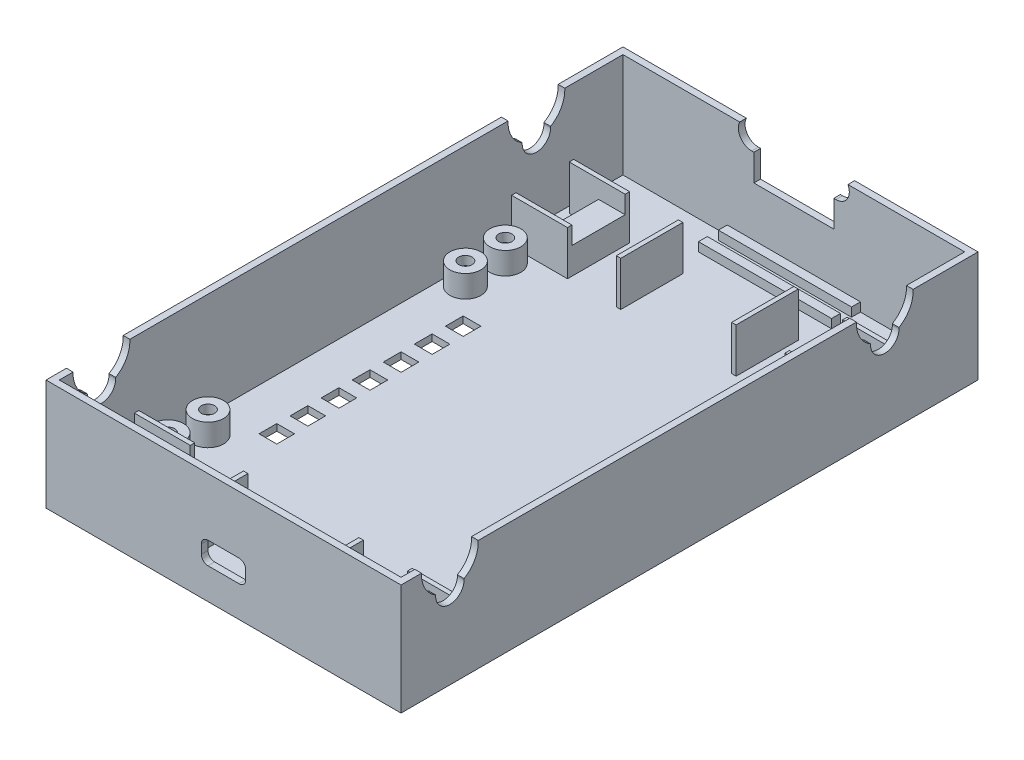
SolidWorks part; units mm, degrees
ref_plane "Спереди" through (0, 0, 0) normal (0, 0, 1) x (1, 0, 0)
ref_plane "Сверху" through (0, 0, 0) normal (0, 1, 0) x (1, 0, 0)
ref_plane "Справа" through (0, 0, 0) normal (1, 0, 0) x (0, 0, -1)
other "Configuration Table"
sketch "Корпус" plane through (0, 0, 0) normal (0, 1, 0) x (1, 0, 0)
  line L1 (40, -65) -> (-40, -65)
  line L2 (40, -65) -> (40, 65)
  line L3 (40, 65) -> (-40, 65)
  line L4 (-40, -65) -> (-40, 65)
  line L5 (40, -65) -> (-40, 65) construction
  line L6 (40, 65) -> (-40, -65) construction
  point P0 (0, 0)
  dimension "D1" = 80
  dimension "D2" = 130
sketch3d "Трехмерный эскиз1" plane through (0, 0, 0) normal (0, 0, 1) x (1, 0, 0)
extrude "Бобышка-Вытянуть1" add sketch "Корпус" along normal blind 25
sketch "Эскиз1" plane through (0, 25, 0) normal (0, 1, 0) x (1, 0, 0)
  line L0 (40, 65) -> (-40, 65) construction
  line L5 (-38.5, 63.5) -> (38.5, 63.5)
  line L6 (-38.5, 63.5) -> (-38.5, -63.5)
  line L7 (-38.5, -63.5) -> (38.5, -63.5)
  line L8 (38.5, 63.5) -> (38.5, -63.5)
  line L9 (-38.5, 63.5) -> (38.5, -63.5) construction
  line L10 (-38.5, -63.5) -> (38.5, 63.5) construction
  line L11 (-40, 65) -> (-40, -65) construction
  point P0 (0, 0)
  dimension "D1" = 1.5
  dimension "D2" = 1.5
extrude "Вырез-Вытянуть1" cut sketch "Эскиз1" against normal offset from surface (23.5 mm away) 1.5 up to face at (0, 0, 0)
sketch "Эскиз2" plane through (0, 0, -63.5) normal (0, 0, 1) x (1, 0, 0)
  line L0 (-14.3, 33.5) -> (14.3, 33.5) construction
  line L5 (-9, 26.7) -> (-9, 32.7)
  line L6 (-9, 32.7) -> (9, 32.7)
  line L7 (14.3, 33.5) -> (14.3, 4.5) construction
  line L8 (14.3, 4.5) -> (-14.3, 4.5) construction
  line L9 (-14.3, 4.5) -> (-14.3, 33.5) construction
  line L10 (0, 33.5) -> (0, 4.5) construction
  line L11 (9, 32.7) -> (9, 26.7)
  line L12 (9, 26.7) -> (9.5, 26.7)
  line L13 (-9, 26.7) -> (-9.5, 26.7)
  line L14 (9.5, 20.7) -> (9, 20.7)
  line L15 (9, 20.7) -> (9, 14.7)
  line L16 (9, 14.7) -> (-9, 14.7)
  line L17 (-9, 14.7) -> (-9, 20.7)
  line L18 (-9, 20.7) -> (-9.5, 20.7)
  line L20 (-12.5, 23.7) -> (12.5, 23.7) construction
  line L21 (-38.5, 1.5) -> (-38.5, 25) construction
  line L22 (38.5, 25) -> (-38.5, 25) construction
  line L23 (-40, 25) -> (40, 25) construction
  line L24 (0, 0) -> (0, 25) construction
  line L25 (-40, 0) -> (40, 0) construction
  arc A4 (-9.5, 26.7) -> (-9.5, 20.7) centre (-9.5, 23.7) ccw
  arc A5 (9.5, 26.7) -> (9.5, 20.7) centre (9.5, 23.7) cw
  point P32 (0, 23.7)
  dimension "D2" = 4.5
  dimension "D3" = 25
  dimension "D4" = 3
  dimension "D5" = 28.6
  dimension "D6" = 28.6
  dimension "D7" = 29
  dimension "D8" = 18
  dimension "D9" = 9.8
  dimension "D10" = 18
  dimension "D11" = 6
  dimension "D12" = 19.2
extrude "Вырез-Вытянуть2" cut sketch "Эскиз2" against normal blind 2
sketch "Эскиз3" plane through (-40, 0, 0) normal (-1, 0, 0) x (0, 0, 1)
  line L1 (-50, 34.7) -> (-38, 34.7) construction
  line L2 (-50, 34.7) -> (-50, 2.5) construction
  line L3 (-50, 2.5) -> (-38, 2.5) construction
  line L4 (-38, 34.7) -> (-38, 2.5) construction
  line L5 (-50, 34.7) -> (-38, 2.5) construction
  line L6 (-50, 2.5) -> (-38, 34.7) construction
  line L7 (-44, 34.7) -> (-44, 2.5) construction
  line L8 (-44, 28.9) -> (-44, 15.7) construction
  line L9 (-47.2, 18.9) -> (-47.2, 19.1574)
  line L10 (-65, 25) -> (-65, 0) construction
  line L12 (-65, 0) -> (65, 0) construction
  line L13 (-47.2, 18.9) -> (-47.2, 19.1574)
  line L14 (-40.8, 18.9) -> (-40.8, 19.1574)
  line L15 (-40.8, 18.9) -> (-40.8, 19.1574)
  line L16 (0, 0) -> (0, 25) construction
  line L17 (-65, 25) -> (65, 25) construction
  arc A1 (-47.2, 18.9) -> (-40.8, 18.9) centre (-44, 18.9) ccw
  arc A2 (-40.8, 19.1574) -> (-47.2, 19.1574) centre (-44, 24.7) ccw
  point P0 (-44, 18.6)
  dimension "D3" = 6.4
  dimension "D4" = 3.2
  dimension "D5" = 5.8
  dimension "D1" = 32.2
  dimension "D2" = 12
  dimension "D6" = 10
  dimension "D7" = 15
  dimension "D8" = 2.5
extrude "Вырез-Вытянуть3" cut sketch "Эскиз3" against normal blind 1.5
sketch "Эскиз5" plane through (-40, 0, 0) normal (-1, 0, 0) x (0, 0, 1)
  line L0 (0, 0) -> (0, 25) construction
  line L1 (-37.607, 25) -> (65, 25) construction
  line L2 (48, 34.7) -> (60, 34.7) construction
  line L3 (48, 34.7) -> (48, 2.5) construction
  line L6 (48, 2.5) -> (60, 2.5) construction
  line L8 (60, 34.7) -> (60, 2.5) construction
  line L9 (48, 34.7) -> (60, 2.5) construction
  line L10 (48, 2.5) -> (60, 34.7) construction
  line L11 (54, 34.7) -> (54, 2.5) construction
  line L12 (54, 28.9) -> (54, 15.7) construction
  line L13 (50.8, 18.9) -> (50.8, 19.1574)
  line L15 (50.8, 18.9) -> (50.8, 19.1574)
  line L16 (57.2, 18.9) -> (57.2, 19.1574)
  line L17 (57.2, 18.9) -> (57.2, 19.1574)
  line L18 (-65, 0) -> (65, 0) construction
  line L19 (65, 25) -> (65, 0) construction
  arc A0 (50.8, 18.9) -> (57.2, 18.9) centre (54, 18.9) ccw
  arc A1 (57.2, 19.1574) -> (50.8, 19.1574) centre (54, 24.7) ccw
  point P5 (54, 18.6)
  dimension "D1" = 32.2
  dimension "D2" = 12
  dimension "D5" = 6.4
  dimension "D6" = 3.2
  dimension "D4" = 10
  dimension "D7" = 5.8
  dimension "D8" = 2.5
  dimension "D9" = 5
extrude "Вырез-Вытянуть4" cut sketch "Эскиз5" against normal up to body (1.5 mm away) from surface at 0 contours A1 L13 A0 L16 starting at face at (-40, 17.2019, -26.4)
sketch "Эскиз6" plane through (40, 0, 0) normal (1, 0, 0) x (0, 0, -1)
  line L0 (-60, 34.7) -> (-48, 34.7) construction
  line L1 (-60, 34.7) -> (-60, 2.5) construction
  line L2 (-60, 2.5) -> (-48, 2.5) construction
  line L3 (-48, 34.7) -> (-48, 2.5) construction
  line L4 (-60, 34.7) -> (-48, 2.5) construction
  line L5 (-60, 2.5) -> (-48, 34.7) construction
  line L6 (-54, 34.7) -> (-54, 2.5) construction
  line L7 (-54, 29.4) -> (-54, 15.7) construction
  line L8 (-57.2, 18.9) -> (-57.2, 19.1574)
  line L9 (-50.8, 18.9) -> (-50.8, 19.1574)
  line L12 (-65, 25) -> (-65, 0) construction
  line L13 (-65, 0) -> (65, 0) construction
  arc A0 (-57.2, 18.9) -> (-50.8, 18.9) centre (-54, 18.9) ccw
  arc A1 (-50.8, 19.1574) -> (-57.2, 19.1574) centre (-54, 24.7) ccw
  point P0 (-54, 18.6)
  dimension "D5" = 6.4
  dimension "D6" = 3.2
  dimension "D1" = 32.2
  dimension "D2" = 12
  dimension "D3" = 5.8
  dimension "D4" = 10
  dimension "D8" = 5
  dimension "D9" = 2.5
extrude "Вырез-Вытянуть5" cut sketch "Эскиз6" against normal up to surface (1.5 mm away) from surface at 0 up to face at (38.5, 13.25, 0) starting at face at (40, 12.5, 0)
sketch "Эскиз9" plane through (40, 0, 0) normal (1, 0, 0) x (0, 0, -1)
  line L0 (38, 34.7) -> (50, 34.7) construction
  line L1 (38, 34.7) -> (38, 2.5) construction
  line L2 (38, 2.5) -> (50, 2.5) construction
  line L3 (50, 34.7) -> (50, 2.5) construction
  line L4 (38, 34.7) -> (50, 2.5) construction
  line L5 (38, 2.5) -> (50, 34.7) construction
  line L6 (44, 34.7) -> (44, 2.5) construction
  line L7 (44, 28.9) -> (44, 15.7) construction
  line L8 (40.8, 18.9) -> (40.8, 19.1574)
  line L9 (40.8, 18.9) -> (40.8, 19.1574)
  line L10 (47.2, 18.9) -> (47.2, 19.1574)
  line L11 (47.2, 18.9) -> (47.2, 19.1574)
  line L12 (65, 25) -> (65, 0) construction
  line L13 (-65, 0) -> (65, 0) construction
  arc A0 (40.8, 18.9) -> (47.2, 18.9) centre (44, 18.9) ccw
  arc A1 (47.2, 19.1574) -> (40.8, 19.1574) centre (44, 24.7) ccw
  point P0 (44, 18.6)
  dimension "D5" = 6.4
  dimension "D6" = 3.2
  dimension "D1" = 32.2
  dimension "D2" = 12
  dimension "D3" = 5.8
  dimension "D4" = 10
  dimension "D8" = 15
  dimension "D9" = 2.5
extrude "Вырез-Вытянуть7" cut sketch "Эскиз9" against normal up to surface (1.5 mm away) from surface at 0 contours A1 L8 A0 L10 up to face at (38.5, 17.5019, 32.4) starting at face at (40, 17.2019, 32.4)
sketch "Эскиз10" plane through (0, 1.5, 0) normal (0, 1, 0) x (1, 0, 0)
  line L0 (-40, 44) -> (40, 44) construction
  line L3 (-40, -54) -> (40, -54) construction
  line L4 (-40, -50.8) -> (-40, -57.2) construction
  line L5 (40, -57.2) -> (40, -50.8) construction
  line L6 (-38.5, -63.5) -> (-38.5, 63.5) construction
  line L7 (-30.5, 38) -> (-24.5, 38)
  line L8 (-30.5, 38) -> (-30.5, 50)
  line L9 (-30.5, 50) -> (-24.5, 50)
  line L10 (-24.5, 38) -> (-24.5, 50)
  line L11 (-30.5, 38) -> (-24.5, 50) construction
  line L12 (-30.5, 50) -> (-24.5, 38) construction
  line L13 (24.5, 38) -> (30.5, 38)
  line L14 (24.5, 38) -> (24.5, 50)
  line L15 (24.5, 50) -> (30.5, 50)
  line L16 (30.5, 38) -> (30.5, 50)
  line L17 (24.5, 38) -> (30.5, 50) construction
  line L18 (24.5, 50) -> (30.5, 38) construction
  line L20 (-30.5, -60) -> (-24.5, -60)
  line L21 (-30.5, -60) -> (-30.5, -48)
  line L22 (-30.5, -48) -> (-24.5, -48)
  line L23 (-24.5, -60) -> (-24.5, -48)
  line L24 (-30.5, -60) -> (-24.5, -48) construction
  line L25 (-30.5, -48) -> (-24.5, -60) construction
  line L26 (24.5, -60) -> (30.5, -60)
  line L27 (24.5, -60) -> (24.5, -48)
  line L28 (24.5, -48) -> (30.5, -48)
  line L29 (30.5, -60) -> (30.5, -48)
  line L30 (24.5, -60) -> (30.5, -48) construction
  line L31 (24.5, -48) -> (30.5, -60) construction
  line L34 (-12.2037, 65) -> (-40, 65) construction
  line L35 (0, 65) -> (0, -65) construction
  line L36 (-9, 65) -> (9, 65) construction
  line L37 (-40, -65) -> (40, -65) construction
  line L38 (38.5, 63.5) -> (38.5, -63.5) construction
  point P4 (0, 44)
  point P12 (-27.5, 44)
  point P19 (27.5, 44)
  point P24 (30.5, 44)
  point P27 (-27.5, -54)
  point P32 (27.5, -54)
  point P37 (30.5, -54)
  point P38 (0, -54)
  point P46 (-30.5, -54)
  dimension "D1" = 12
  dimension "D2" = 98
  dimension "D3" = 6
  dimension "D4" = 6
  dimension "D5" = 12
  dimension "D6" = 8
  dimension "D7" = 12
  dimension "D8" = 6
  dimension "D9" = 6
  dimension "D10" = 12
  dimension "D11" = 8
  dimension "D12" = 8
  dimension "D13" = 21
  dimension "D14" = 8
extrude "Бобышка-Вытянуть2" add sketch "Эскиз10" along normal blind 6
sketch "Эскиз11" plane through (0, 1.5, 0) normal (0, 1, 0) x (1, 0, 0)
  line L0 (-24.5, 50) -> (-24.5, 51)
  line L1 (-24.5, 51) -> (-37.1, 51)
  line L2 (37.1, 50) -> (37.1, 51)
  line L3 (-24.5, 50) -> (-37.1, 50)
  line L4 (-37.1, 50) -> (-37.1, 51)
  line L5 (-24.5, 38) -> (-37.1, 38)
  line L6 (37.1, 51) -> (24.5, 51)
  line L7 (-37.1, 38) -> (-37.1, 37)
  line L8 (37.1, 50) -> (24.5, 50)
  line L9 (-37.1, 37) -> (-24.5, 37)
  line L10 (-24.5, 37) -> (-24.5, 38)
  line L11 (24.5, 50) -> (24.5, 51)
  line L12 (37.1, 38) -> (24.5, 38)
  line L13 (24.5, 38) -> (24.5, 37)
  line L14 (24.5, 37) -> (37.1, 37)
  line L15 (37.1, 37) -> (37.1, 38)
  line L16 (37.1, -48) -> (37.1, -47)
  line L17 (37.1, -47) -> (24.5, -47)
  line L18 (37.1, -48) -> (24.5, -48)
  line L19 (24.5, -48) -> (24.5, -47)
  line L20 (37.1, -60) -> (24.5, -60)
  line L21 (24.5, -60) -> (24.5, -61)
  line L22 (24.5, -61) -> (37.1, -61)
  line L23 (37.1, -61) -> (37.1, -60)
  line L24 (-24.5, -48) -> (-24.5, -47)
  line L25 (-24.5, -47) -> (-37.1, -47)
  line L26 (-24.5, -48) -> (-37.1, -48)
  line L27 (-37.1, -48) -> (-37.1, -47)
  line L28 (-24.5, -60) -> (-37.1, -60)
  line L29 (-37.1, -60) -> (-37.1, -61)
  line L30 (-37.1, -61) -> (-24.5, -61)
  line L31 (-24.5, -61) -> (-24.5, -60)
  dimension "D1" = 1
  dimension "D2" = 12.6
  dimension "D3" = 12.6
  dimension "D4" = 1
  dimension "D5" = 12.6
  dimension "D6" = 1
  dimension "D7" = 12.6
  dimension "D8" = 1
extrude "Бобышка-Вытянуть3" add sketch "Эскиз11" along normal blind 10
sketch "Эскиз13" plane through (0, 1.5, 0) normal (0, 1, 0) x (1, 0, 0)
  line L0 (-10, -63.5) -> (10, -63.5) construction
  line L1 (-40, -5) -> (40, -5) construction
  line L2 (10, -63.5) -> (10, -36.5) construction
  line L3 (10, -36.5) -> (37, -36.5) construction
  line L4 (37, -36.5) -> (37, 26.5) construction
  line L5 (37, 26.5) -> (-37, 26.5) construction
  line L6 (-40, -65) -> (40, -65) construction
  line L7 (-37, 26.5) -> (-37, -36.5) construction
  line L8 (-37, -36.5) -> (-10, -36.5) construction
  line L9 (-10, -36.5) -> (-10, -63.5) construction
  line L10 (-38.5, -63.5) -> (38.5, -63.5) construction
  line L11 (-40, 44) -> (-40, -54) construction
  line L12 (-40, 47.2) -> (-40, 40.8) construction
  line L14 (-40, -50.8) -> (-40, -57.2) construction
  circle A0 centre (-34.5, 24) radius 3.5
  circle A2 centre (34.5, 24) radius 3.5
  circle A3 centre (-34.5, -34) radius 3.5
  circle A4 centre (34.5, -34) radius 3.5
  circle A8 centre (-34.5, 33) radius 3.5
  circle A9 centre (34.5, 33) radius 3.5
  circle A10 centre (-34.5, -43) radius 3.5
  circle A11 centre (34.5, -43) radius 3.5
  circle A12 centre (0, -54) radius 3.5
  point P2 (0, -63.5)
  point P9 (0, -63.5)
  point P45 (-40, -5)
  dimension "D5" = 29
  dimension "D6" = 2.5
  dimension "D8" = 7
  dimension "D11" = 7
  dimension "D16" = 7
  dimension "D17" = 7
  dimension "D18" = 27
  dimension "D25" = 7
  dimension "D26" = 7
  dimension "D28" = 7
  dimension "D30" = 7
  dimension "D1" = 20
  dimension "D4" = 29
  dimension "D7" = 2.5
  dimension "D9" = 2.5
  dimension "D10" = 2.5
  dimension "D12" = 2.5
  dimension "D13" = 2.5
  dimension "D14" = 2.5
  dimension "D15" = 2.5
  dimension "D19" = 9.5
  dimension "D23" = 29
  dimension "D24" = 9
  dimension "D27" = 9
  dimension "D29" = 9
  dimension "D31" = 9
  dimension "D32" = 22
  dimension "D33" = 69
  dimension "D34" = 76
extrude "Бобышка-Вытянуть4" add sketch "Эскиз13" along normal blind 5
sketch "Эскиз14" plane through (0, 0, 0) normal (0, -1, 0) x (1, 0, 0)
  circle A2 centre (-34.5, 34) radius 2.5
  circle A3 centre (34.5, 34) radius 2.5
  circle A4 centre (-34.5, -24) radius 2.5
  circle A5 centre (34.5, -24) radius 2.5
  circle A6 centre (-34.5, -33) radius 2.5
  circle A7 centre (34.5, -33) radius 2.5
  circle A8 centre (34.5, 43) radius 2.5
  circle A9 centre (-34.5, 43) radius 2.5
  circle A10 centre (0, 54) radius 2.5
  dimension "D2" = 5
  dimension "D3" = 5
  dimension "D4" = 5
  dimension "D5" = 5
  dimension "D6" = 5
  dimension "D7" = 5
  dimension "D8" = 5
  dimension "D9" = 5
  dimension "D10" = 5
extrude "Вырез-Вытянуть8" cut sketch "Эскиз14" against normal offset from surface (4.5 mm away) 2 up to face at (-34.5, 6.5, -20.5)
sketch "Эскиз15" plane through (0, 6.5, 0) normal (0, 1, 0) x (1, 0, 0)
  circle A0 centre (-34.5, 24) radius 1.5
  circle A1 centre (34.5, 24) radius 1.5
  circle A2 centre (-34.5, -34) radius 1.5
  circle A3 centre (34.5, -34) radius 1.5
  circle A6 centre (-34.5, 33) radius 1.5
  circle A7 centre (34.5, 33) radius 1.5
  circle A9 centre (-34.5, -43) radius 1.5
  circle A11 centre (34.5, -43) radius 1.5
  circle A12 centre (0, -54) radius 1.5
  dimension "D1" = 3
  dimension "D2" = 3
  dimension "D3" = 3
  dimension "D4" = 3
  dimension "D5" = 3
  dimension "D7" = 3
  dimension "D8" = 3
  dimension "D9" = 3
  dimension "D10" = 3
extrude "Вырез-Вытянуть9" cut sketch "Эскиз15" against normal up to next
fillet "Скругление1" radius 1 9 edges at (34.5, 0, 31.5) (-34.5, 0, 31.5) (-34.5, 0, -26.5) (34.5, 0, -26.5) (34.5, 0, 40.5) (-34.5, 0, 40.5) (-34.5, 0, -35.5) (34.5, 0, -35.5) (0, 0, 51.5)
sketch "Эскиз16" plane through (0, 1.5, 0) normal (0, 1, 0) x (1, 0, 0)
  line L0 (-29, 11) -> (-25, 11)
  line L5 (-29, 18) -> (-25, 18)
  line L6 (-29, 18) -> (-29, 14)
  line L7 (-29, 14) -> (-25, 14)
  line L8 (-25, 18) -> (-25, 14)
  line L9 (-29, 18) -> (-25, 14) construction
  line L10 (-29, 14) -> (-25, 18) construction
  line L11 (-29, 11) -> (-29, 7)
  line L12 (-29, 7) -> (-25, 7)
  line L13 (-25, 11) -> (-25, 7)
  line L14 (-29, 11) -> (-25, 7) construction
  line L15 (-29, 7) -> (-25, 11) construction
  line L16 (0, 65) -> (0, -65) construction
  line L17 (-9, 65) -> (9, 65) construction
  line L18 (-40, -65) -> (40, -65) construction
  line L19 (-29, -3) -> (-25, -3)
  line L20 (-29, 4) -> (-25, 4)
  line L21 (-29, 4) -> (-29, 0)
  line L22 (-29, 0) -> (-25, 0)
  line L23 (-25, 4) -> (-25, 0)
  line L24 (-29, 4) -> (-25, 0) construction
  line L25 (-29, 0) -> (-25, 4) construction
  line L26 (-29, -3) -> (-29, -7)
  line L27 (-29, -7) -> (-25, -7)
  line L28 (-25, -3) -> (-25, -7)
  line L29 (-29, -3) -> (-25, -7) construction
  line L30 (-29, -7) -> (-25, -3) construction
  line L31 (-29, -17) -> (-25, -17)
  line L32 (-29, -10) -> (-25, -10)
  line L33 (-29, -10) -> (-29, -14)
  line L34 (-29, -14) -> (-25, -14)
  line L35 (-25, -10) -> (-25, -14)
  line L36 (-29, -10) -> (-25, -14) construction
  line L37 (-29, -14) -> (-25, -10) construction
  line L38 (-29, -17) -> (-29, -21)
  line L39 (-29, -21) -> (-25, -21)
  line L40 (-25, -17) -> (-25, -21)
  line L41 (-29, -17) -> (-25, -21) construction
  line L42 (-29, -21) -> (-25, -17) construction
  line L44 (-29, -24) -> (-25, -24)
  line L45 (-29, -24) -> (-29, -28)
  line L46 (-29, -28) -> (-25, -28)
  line L47 (-25, -24) -> (-25, -28)
  line L48 (-29, -24) -> (-25, -28) construction
  line L49 (-29, -28) -> (-25, -24) construction
  line L53 (-40, -5) -> (40, -5) construction
  line L56 (29, -28) -> (25, -24) construction
  line L57 (29, -24) -> (25, -28) construction
  line L58 (29, -21) -> (25, -17) construction
  line L59 (29, -17) -> (25, -21) construction
  line L60 (29, -14) -> (25, -10) construction
  line L61 (29, -10) -> (25, -14) construction
  line L62 (29, -7) -> (25, -3) construction
  line L63 (29, -3) -> (25, -7) construction
  line L64 (29, 0) -> (25, 4) construction
  line L65 (29, 4) -> (25, 0) construction
  line L66 (29, 7) -> (25, 11) construction
  line L67 (29, 11) -> (25, 7) construction
  line L68 (29, 14) -> (25, 18) construction
  line L69 (29, 18) -> (25, 14) construction
  line L70 (25, -24) -> (25, -28)
  line L71 (29, -28) -> (25, -28)
  line L72 (29, -24) -> (29, -28)
  line L73 (29, -24) -> (25, -24)
  line L74 (25, -17) -> (25, -21)
  line L75 (29, -21) -> (25, -21)
  line L76 (29, -17) -> (29, -21)
  line L77 (25, -10) -> (25, -14)
  line L78 (29, -14) -> (25, -14)
  line L79 (29, -10) -> (29, -14)
  line L80 (29, -10) -> (25, -10)
  line L81 (29, -17) -> (25, -17)
  line L82 (25, -3) -> (25, -7)
  line L83 (29, -7) -> (25, -7)
  line L84 (29, -3) -> (29, -7)
  line L85 (25, 4) -> (25, 0)
  line L86 (29, 0) -> (25, 0)
  line L87 (29, 4) -> (29, 0)
  line L88 (29, 4) -> (25, 4)
  line L89 (29, -3) -> (25, -3)
  line L90 (25, 11) -> (25, 7)
  line L91 (29, 7) -> (25, 7)
  line L92 (29, 11) -> (29, 7)
  line L93 (25, 18) -> (25, 14)
  line L94 (29, 14) -> (25, 14)
  line L95 (29, 18) -> (29, 14)
  line L96 (29, 18) -> (25, 18)
  line L97 (29, 11) -> (25, 11)
  point P0 (-27, 16)
  point P5 (-27, 9)
  point P10 (-27, 2)
  point P21 (-27, -5)
  point P26 (-27, -12)
  point P31 (-27, -19)
  point P36 (-27, -26)
  point P76 (27, -26)
  point P77 (27, -19)
  point P78 (27, -12)
  point P79 (27, -5)
  point P80 (27, 2)
  point P81 (27, 9)
  point P82 (27, 16)
  dimension "D1" = 4
  dimension "D2" = 4
  dimension "D3" = 4
  dimension "D4" = 3
  dimension "D5" = 4
  dimension "D6" = 25
  dimension "D7" = 25
  dimension "D8" = 4
  dimension "D9" = 4
  dimension "D10" = 4
  dimension "D11" = 3
  dimension "D12" = 4
  dimension "D13" = 4
  dimension "D14" = 4
  dimension "D15" = 4
  dimension "D16" = 3
  dimension "D17" = 4
  dimension "D18" = 4
  dimension "D22" = 25
  dimension "D23" = 25
  dimension "D24" = 25
  dimension "D25" = 25
  dimension "D26" = 25
  dimension "D28" = 3
  dimension "D29" = 3
  dimension "D30" = 3
  dimension "D31" = 4
extrude "Вырез-Вытянуть10" cut sketch "Эскиз16" against normal up to next
sketch "Эскиз17" plane through (0, 0, 65) normal (0, 0, 1) x (1, 0, 0)
  line L0 (0, 25) -> (0, 0) construction
  line L1 (-40, 25) -> (40, 25) construction
  line L16 (-40, 0) -> (40, 0) construction
  line L17 (-3.5, 12) -> (3.5, 12)
  line L18 (-5, 10.5) -> (-5, 8.5)
  line L19 (-3.5, 7) -> (3.5, 7)
  line L20 (5, 10.5) -> (5, 8.5)
  arc A6 (-5, 10.5) -> (-3.5, 12) centre (-3.5, 10.5) cw
  arc A7 (3.5, 12) -> (5, 10.5) centre (3.5, 10.5) cw
  arc A8 (-3.5, 7) -> (-5, 8.5) centre (-3.5, 8.5) cw
  arc A9 (5, 8.5) -> (3.5, 7) centre (3.5, 8.5) cw
  point P5 (0, 9.5)
  dimension "D4" = 1.5
  dimension "D1" = 10
  dimension "D2" = 5
  dimension "D3" = 7
extrude "Вырез-Вытянуть12" cut sketch "Эскиз17" against normal up to surface (1.5 mm away) up to face at (0, 13.25, 63.5)
sketch "Эскиз18" plane through (0, 1.5, 0) normal (0, 1, 0) x (1, 0, 0)
  line L0 (0, 65) -> (0, -65) construction
  line L1 (-15, 63.5) -> (15, 63.5)
  line L2 (-15, 63.5) -> (-15, 61.5)
  line L3 (-15, 61.5) -> (15, 61.5)
  line L4 (15, 63.5) -> (15, 61.5)
  line L5 (-15, 63.5) -> (15, 61.5) construction
  line L6 (-15, 61.5) -> (15, 63.5) construction
  line L7 (-9, 65) -> (9, 65) construction
  line L8 (-40, -65) -> (40, -65) construction
  line L9 (-38.5, 63.5) -> (38.5, 63.5) construction
  line L11 (-15, 59) -> (15, 59)
  line L12 (-15, 59) -> (-15, 57)
  line L13 (-15, 57) -> (15, 57)
  line L14 (15, 59) -> (15, 57)
  line L15 (-15, 59) -> (15, 57) construction
  line L16 (-15, 57) -> (15, 59) construction
  point P0 (0, 62.5)
  point P11 (0, 63.5)
  point P14 (0, 58)
  dimension "D1" = 2
  dimension "D2" = 30
  dimension "D3" = 2
  dimension "D4" = 2.5
extrude "Бобышка-Вытянуть5" add sketch "Эскиз18" along normal blind 2
sketch "Эскиз19" plane through (0, 1.5, 0) normal (0, 1, 0) x (1, 0, 0)
  line L0 (-40, 44) -> (40, 44) construction
  line L1 (-13.5, 51) -> (-12.5, 51)
  line L2 (-13.5, 51) -> (-13.5, 37)
  line L3 (-13.5, 37) -> (-12.5, 37)
  line L4 (-12.5, 51) -> (-12.5, 37)
  line L5 (-13.5, 51) -> (-12.5, 37) construction
  line L6 (-13.5, 37) -> (-12.5, 51) construction
  line L7 (40, 40.8) -> (40, 47.2) construction
  line L8 (-38.5, -63.5) -> (-38.5, 63.5) construction
  line L9 (12.5, 51) -> (13.5, 51)
  line L10 (12.5, 51) -> (12.5, 37)
  line L11 (12.5, 37) -> (13.5, 37)
  line L12 (13.5, 51) -> (13.5, 37)
  line L13 (12.5, 51) -> (13.5, 37) construction
  line L14 (12.5, 37) -> (13.5, 51) construction
  line L15 (38.5, 50.393) -> (38.5, 63.5) construction
  line L16 (-40, -54) -> (40, -54) construction
  line L17 (40, -57.2) -> (40, -50.8) construction
  line L18 (-13.5, -47) -> (-12.5, -47)
  line L19 (-13.5, -47) -> (-13.5, -61)
  line L20 (-13.5, -61) -> (-12.5, -61)
  line L21 (-12.5, -47) -> (-12.5, -61)
  line L22 (-13.5, -47) -> (-12.5, -61) construction
  line L23 (-13.5, -61) -> (-12.5, -47) construction
  line L24 (12.5, -47) -> (13.5, -47)
  line L25 (12.5, -47) -> (12.5, -61)
  line L26 (12.5, -61) -> (13.5, -61)
  line L27 (13.5, -47) -> (13.5, -61)
  line L28 (12.5, -47) -> (13.5, -61) construction
  line L29 (12.5, -61) -> (13.5, -47) construction
  line L30 (38.5, -47.607) -> (38.5, 37.607) construction
  point P0 (-13, 44)
  point P13 (13, 44)
  point P24 (-13, -54)
  point P29 (13, -54)
  dimension "D1" = 14
  dimension "D2" = 1
  dimension "D3" = 25
  dimension "D4" = 14
  dimension "D5" = 1
  dimension "D6" = 25
  dimension "D7" = 14
  dimension "D8" = 1
  dimension "D9" = 14
  dimension "D10" = 1
  dimension "D11" = 25
  dimension "D12" = 25
extrude "Бобышка-Вытянуть6" add sketch "Эскиз19" along normal blind 10
